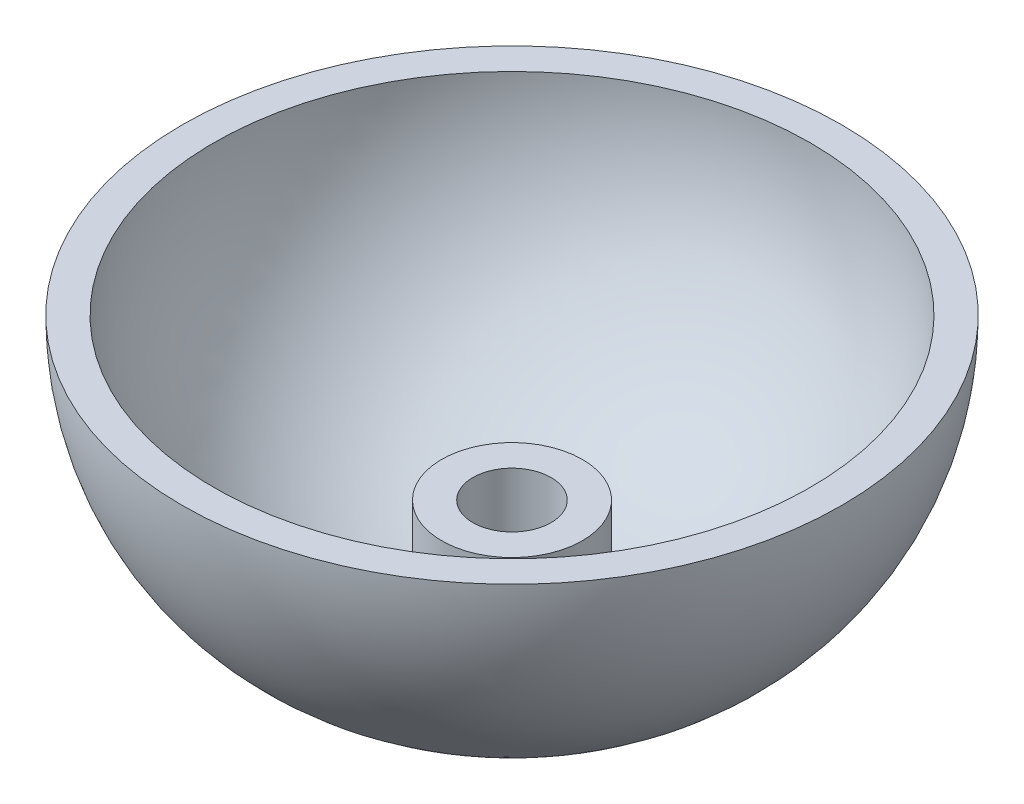
SolidWorks part; units mm, degrees
material "Custom Plastic"
ref_plane "Front Plane" through (0, 0, 0) normal (0, 0, 1) x (1, 0, 0)
ref_plane "Top Plane" through (0, 0, 0) normal (0, 1, 0) x (1, 0, 0)
ref_plane "Right Plane" through (0, 0, 0) normal (1, 0, 0) x (0, 0, -1)
sketch "Sketch2" plane through (0, 0, 0) normal (0, 0, 1) x (1, 0, 0)
  line L0 (0, 0) -> (0, 21.4801) construction
  line L1 (-1.5, 5) -> (-1.5, 0)
  arc A0 (-12.642, 11.142) -> (-1.5, 0) centre (-1.5, 11.142) ccw
  dimension "D1" = 3
  dimension "D2" = 5
revolve "Revolve-Thin1" add sketch "Sketch2" angle 360 about L0
